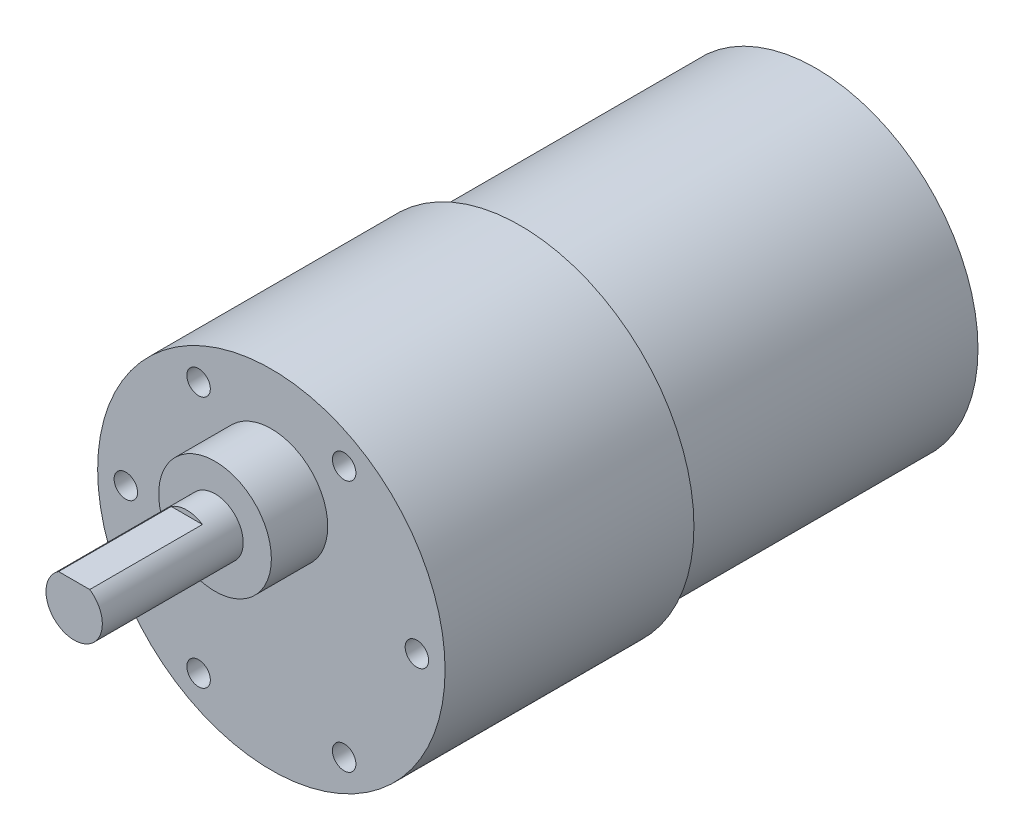
SolidWorks part; units mm, degrees
ref_plane "Front Plane" through (0, 0, 0) normal (0, 0, 1) x (1, 0, 0)
ref_plane "Top Plane" through (0, 0, 0) normal (0, 1, 0) x (1, 0, 0)
ref_plane "Right Plane" through (0, 0, 0) normal (1, 0, 0) x (0, 0, -1)
sketch "Sketch1" plane through (0, 0, 0) normal (0, 0, 1) x (1, 0, 0)
  circle A0 centre (0, 0) radius 18.5
  dimension "D1" = 37
extrude "Boss-Extrude1" add sketch "Sketch1" along normal mid plane 58
sketch "Sketch2" plane through (0, 0, -29) normal (0, 0, -1) x (-1, 0, 0)
  circle A0 centre (0, 0) radius 17.25
  circle A1 centre (0, 0) radius 18.5 construction
  circle A2 centre (0, 0) radius 18.5
  dimension "D1" = 34.5
extrude "Cut-Extrude1" cut sketch "Sketch2" against normal blind 31.5
sketch "Sketch3" plane through (0, 0, 29) normal (0, 0, 1) x (1, 0, 0)
  circle A0 centre (0, 7) radius 6
  dimension "D1" = 12
  dimension "D2" = 7
extrude "Boss-Extrude2" add sketch "Sketch3" along normal blind 6
sketch "Sketch4" plane through (0, 0, 35) normal (0, 0, 1) x (1, 0, 0)
  circle A0 centre (0, 7) radius 3
  dimension "D1" = 6
extrude "Boss-Extrude3" add sketch "Sketch4" along normal blind 15
sketch "Sketch5" plane through (0, 0, 50) normal (0, 0, 1) x (1, 0, 0)
  line L0 (-1.6583, 9.5) -> (1.6583, 9.5)
  circle A0 centre (0, 7) radius 3 construction
  arc A1 (1.6583, 9.5) -> (-1.6583, 9.5) centre (0, 7) ccw
  point P5 (0, 4)
  dimension "D1" = 5.5
extrude "Cut-Extrude2" cut sketch "Sketch5" against normal blind 12
hole_wizard "M3x0.5 Tapped Hole1" positions "Sketch6" profile "Sketch7" tap size "M3x0.5" standard "ANSI Metric"
sketch "Sketch6" plane through (0, 0, 29) normal (0, 0, 1) x (1, 0, 0)
  line L0 (0, 0) -> (0, 15.5) construction
  line L2 (0, 0) -> (7.75, 13.4234) construction
  circle A0 centre (0, 0) radius 15.5 construction
  point P12 (7.75, 13.4234)
  dimension "D1" = 31
  dimension "D2" = 30
sketch "Sketch7" plane through (7.75, 13.4234, 29) normal (1, 0, 0) x (0, -1, 0)
  line L0 (0, 0) -> (0, 4.2511)
  line L1 (0, 4.2511) -> (1.25, 3.5)
  line L2 (1.25, 3.5) -> (1.25, 0)
  line L5 (1.25, 0) -> (0, 0)
  line L10 (0, 4.2511) -> (-1.25, 3.5) construction
  line L11 (0, -6.35) -> (0, 107.95) construction
  dimension "Tap Drill Dia." = 2.5
  dimension "Tap Drill Depth" = 3.5
  dimension "Drill Angle" = 118
cosmetic thread "Hole Thread1" parameters "D1"=3.5, "D2"=3
pattern_circular "CirPattern1" count 6 over 360 about axis through (0, 0, 0) along (0, 0, 1) of "M3x0.5 Tapped Hole1"
